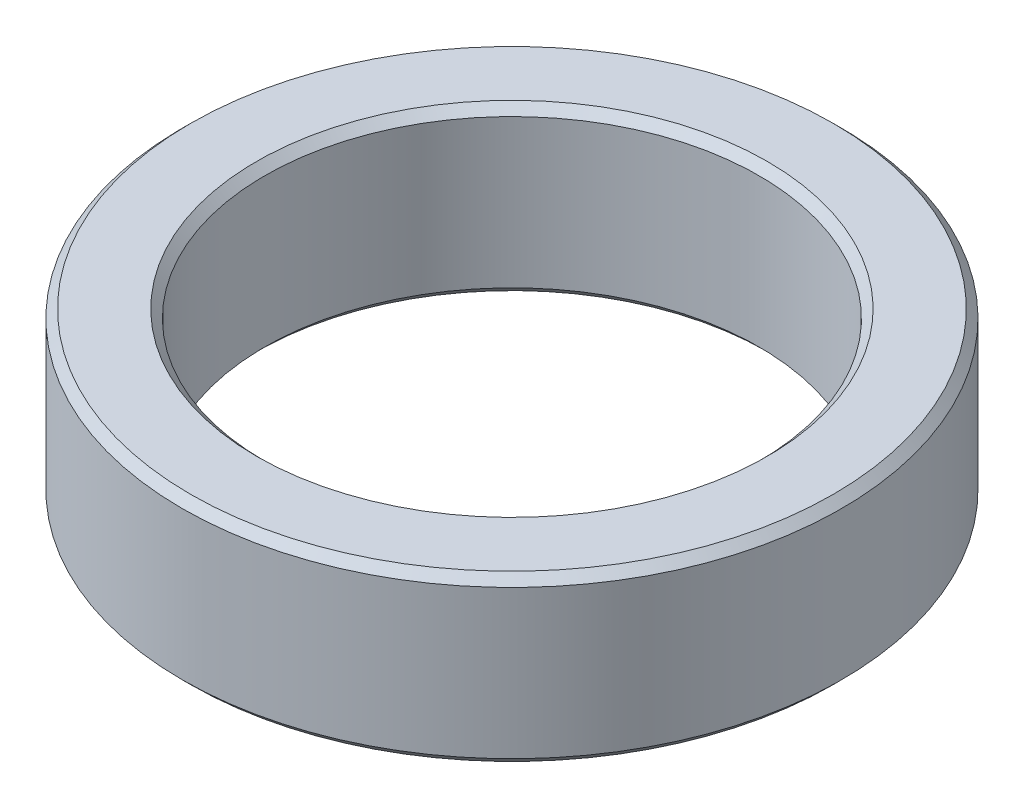
SolidWorks part; units mm, degrees
ref_plane "Front Plane" through (0, 0, 0) normal (0, 0, 1) x (1, 0, 0)
ref_plane "Top Plane" through (0, 0, 0) normal (0, 1, 0) x (1, 0, 0)
ref_plane "Right Plane" through (0, 0, 0) normal (1, 0, 0) x (0, 0, -1)
sketch "Sketch1" plane through (0, 0, 0) normal (0, 1, 0) x (1, 0, 0)
  circle A0 centre (0, 0) radius 20
  circle A1 centre (0, 0) radius 15
  dimension "D1" = 40
  dimension "D2" = 30
extrude "Boss-Extrude1" add sketch "Sketch1" along normal mid plane 10
chamfer "Chamfer1" distance 0.5 angle 45 4 edges at (0, -5, 15) (0, -5, 20) (0, 5, 20) (0, 5, 15)
